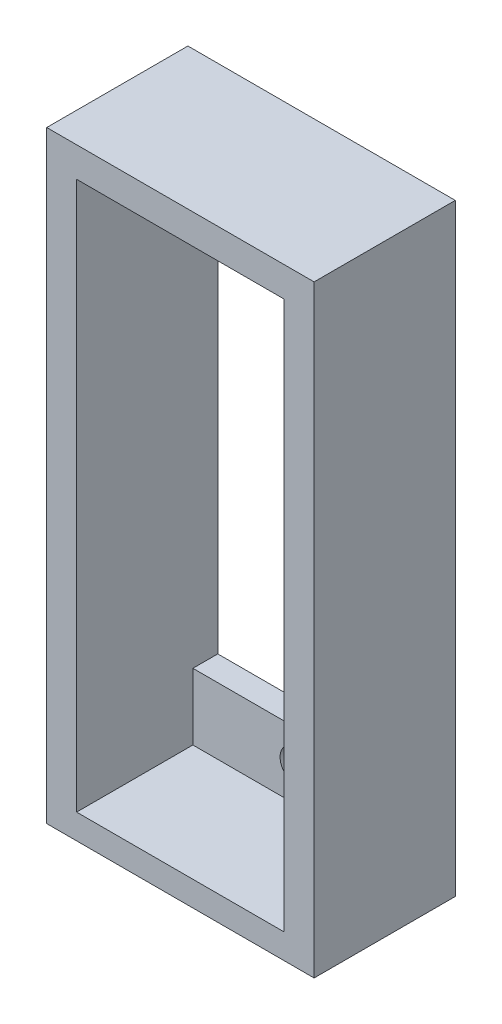
SolidWorks part; units mm, degrees
ref_plane "Alzado" through (0, 0, 0) normal (0, 0, 1) x (1, 0, 0)
ref_plane "Planta" through (0, 0, 0) normal (0, 1, 0) x (1, 0, 0)
ref_plane "Vista lateral" through (0, 0, 0) normal (1, 0, 0) x (0, 0, -1)
sketch "Croquis1" plane through (0, 0, 0) normal (0, 0, 1) x (1, 0, 0)
  circle A0 centre (-51.2357, 9.7866) radius 31.5
  dimension "D1" = 63
extrude "Saliente-Extruir1" add sketch "Croquis1" along normal blind 2.4
sketch "Croquis2" plane through (0, 0, 2.4) normal (0, 0, 1) x (1, 0, 0)
  line L0 (-51.2357, 9.7866) -> (-51.2357, -21.7134) construction
  line L1 (-51.2357, 9.7866) -> (-51.2357, 14.4866) construction
  line L2 (-51.2357, 14.4866) -> (-51.2357, 19.4866) construction
  line L3 (-51.2357, 19.4866) -> (-51.2357, 21.2866) construction
  line L4 (-51.2357, 21.2866) -> (-57.4857, 21.2866) construction
  line L6 (-57.4857, 21.2866) -> (-44.9857, 21.2866)
  line L7 (-57.4857, 21.2866) -> (-57.4857, -11.7134)
  line L8 (-57.4857, -11.7134) -> (-44.9857, -11.7134)
  line L9 (-44.9857, 21.2866) -> (-44.9857, -11.7134)
  line L14 (-59.2857, 23.0866) -> (-43.1857, 23.0866)
  line L15 (-59.2857, 23.0866) -> (-59.2857, -13.2134)
  line L16 (-59.2857, -13.2134) -> (-43.1857, -13.2134)
  line L17 (-43.1857, 23.0866) -> (-43.1857, -13.2134)
  circle A0 centre (-51.2357, 9.7866) radius 31.5 construction
  dimension "D2" = 5
  dimension "D3" = 1.8
  dimension "D4" = 6.25
  dimension "D5" = 12.5
  dimension "D6" = 33
  dimension "D7" = 1.8
  dimension "D8" = 1.8
  dimension "D9" = 1.8
  dimension "D10" = 1.5
  dimension "D11" = 8.5
extrude "Saliente-Extruir2" add sketch "Croquis2" along normal blind 22.5
sketch "Croquis5" plane through (0, 0, 2.4) normal (0, 0, 1) x (1, 0, 0)
  line L1 (-59.2857, 23.0866) -> (-43.1857, 23.0866)
  line L2 (-59.2857, 23.0866) -> (-59.2857, -13.2134)
  line L3 (-59.2857, -13.2134) -> (-43.1857, -13.2134)
  line L4 (-43.1857, 23.0866) -> (-43.1857, -13.2134)
extrude "Cortar-Extruir2" cut sketch "Croquis5" against normal blind 9
sketch "Croquis6" plane through (0, 0, 0) normal (0, 0, -1) x (-1, 0, 0)
  line L6 (51.2357, 9.7866) -> (73.5095, 32.0605) construction
  line L7 (73.5095, 32.0605) -> (73.5095, -12.4873) construction
  line L8 (73.5095, -12.4873) -> (28.9618, 32.0605) construction
  line L9 (28.9618, 32.0605) -> (28.9618, -12.4873) construction
  line L10 (28.9618, -12.4873) -> (51.2357, 9.7866) construction
  line L11 (51.2357, 23.0866) -> (53.2357, 23.0866)
  line L12 (43.1857, 23.0866) -> (59.2857, 23.0866) construction
  line L13 (53.2357, 23.0866) -> (53.2357, 43.0866)
  line L14 (53.2357, 43.0866) -> (49.2357, 43.0866)
  line L15 (49.2357, 43.0866) -> (49.2357, 23.0866)
  line L16 (49.2357, 23.0866) -> (51.2357, 23.0866)
  circle A0 centre (51.2357, 9.7866) radius 31.5 construction
  circle A1 centre (34.6187, 26.4036) radius 1.5
  circle A2 centre (67.8527, 26.4036) radius 1.5
  circle A3 centre (67.8527, -6.8304) radius 1.5
  circle A4 centre (34.6187, -6.8304) radius 1.5
  dimension "D3" = 8
  dimension "D1" = 20
  dimension "D2" = 4
extrude "Cortar-Extruir3" cut sketch "Croquis6" against normal blind 2.4
sketch "Croquis7" plane through (0, 21.2866, 0) normal (0, -1, 0) x (1, 0, 0)
  line L0 (-57.4857, 24.9) -> (-57.4857, 2.4) construction
  line L1 (-57.4857, 17.9) -> (-44.9857, 17.9)
  line L2 (-57.4857, 17.9) -> (-57.4857, 8.9)
  line L3 (-57.4857, 8.9) -> (-44.9857, 8.9)
  line L4 (-44.9857, 17.9) -> (-44.9857, 8.9)
  line L5 (-44.9857, 24.9) -> (-44.9857, 2.4) construction
  line L6 (-44.9857, 24.9) -> (-57.4857, 24.9) construction
  dimension "D1" = 9
  dimension "D2" = 7
extrude "Saliente-Extruir3" add sketch "Croquis7" along normal up to vertex (33 mm away)
sketch "Croquis8" plane through (0, 0, 17.9) normal (0, 0, 1) x (1, 0, 0)
  line L0 (-44.9857, -11.7134) -> (-44.9857, 21.2866) construction
  line L1 (-44.9857, -7.7134) -> (-57.4857, -7.7134)
  line L2 (-44.9857, -7.7134) -> (-44.9857, 15.2866)
  line L4 (-57.4857, -7.7134) -> (-57.4857, 15.2866)
  line L5 (-57.4857, -11.7134) -> (-57.4857, 21.2866) construction
  line L6 (-44.9857, -11.7134) -> (-57.4857, -11.7134) construction
  line L9 (-44.9857, 15.2866) -> (-49.2357, 15.2866)
  line L10 (-49.2357, 15.2866) -> (-49.2357, 17.2866)
  line L11 (-49.2357, 17.2866) -> (-53.2357, 17.2866)
  line L12 (-53.2357, 17.2866) -> (-53.2357, 15.2866)
  line L13 (-53.2357, 15.2866) -> (-57.4857, 15.2866)
  line L14 (-44.9857, 21.2866) -> (-57.4857, 21.2866) construction
  circle A0 centre (-51.2357, -9.7134) radius 1
  circle A1 centre (-51.2357, 18.3366) radius 1
  dimension "D3" = 2
  dimension "D6" = 2.95
  dimension "D1" = 4
  dimension "D2" = 6
  dimension "D4" = 4
  dimension "D5" = 2
  dimension "D7" = 2
extrude "Cortar-Extruir5" cut sketch "Croquis8" against normal blind 9
sketch "Croquis9" plane through (-44.9857, 0, 0) normal (-1, 0, 0) x (0, 0, 1)
  line L0 (8.9, -7.7134) -> (3.9, -11.7134)
  line L1 (8.9, -11.7134) -> (2.4, -11.7134) construction
  line L2 (3.9, -11.7134) -> (8.9, -11.7134)
  line L3 (8.9, -11.7134) -> (8.9, -7.7134)
  line L4 (8.9, 15.2866) -> (4.1, 21.2866)
  line L5 (8.9, 21.2866) -> (2.4, 21.2866) construction
  line L6 (4.1, 21.2866) -> (8.9, 21.2866)
  line L7 (8.9, 21.2866) -> (8.9, 15.2866)
extrude "Saliente-Extruir4" add sketch "Croquis9" along normal up to vertex (12.5 mm away)
sketch "Croquis10" plane through (0, 0, 8.9) normal (0, 0, 1) x (1, 0, 0)
  line L1 (-53.2357, 15.2866) -> (-49.2357, 15.2866)
  line L2 (-53.2357, 15.2866) -> (-53.2357, 17.2866)
  line L3 (-53.2357, 17.2866) -> (-49.2357, 17.2866)
  line L4 (-49.2357, 15.2866) -> (-49.2357, 17.2866)
extrude "Cortar-Extruir6" cut sketch "Croquis10" against normal blind 9
sketch "Croquis11" plane through (0, 0, 2.4) normal (0, 0, -1) x (-1, 0, 0)
  line L0 (49.2357, 23.0866) -> (43.1857, 23.0866)
  line L1 (43.1857, 23.0866) -> (43.1857, -13.2134)
  line L2 (43.1857, -13.2134) -> (59.2857, -13.2134)
  line L3 (59.2857, -13.2134) -> (59.2857, 23.0866)
  line L4 (59.2857, 23.0866) -> (53.2357, 23.0866)
  line L5 (53.2357, 23.0866) -> (53.2357, 21.2866)
  line L6 (44.9857, 21.2866) -> (57.4857, 21.2866) construction
  line L7 (53.2357, 21.2866) -> (57.4857, 21.2866)
  line L8 (57.4857, 21.2866) -> (57.4857, 10.5866)
  line L9 (57.4857, 21.2866) -> (57.4857, -11.7134) construction
  line L10 (57.4857, 10.5866) -> (44.9857, 10.5866)
  line L11 (44.9857, -11.7134) -> (44.9857, 21.2866) construction
  line L12 (44.9857, 10.5866) -> (44.9857, 21.2866)
  line L13 (44.9857, 21.2866) -> (49.2357, 21.2866)
  line L14 (49.2357, 21.2866) -> (49.2357, 23.0866)
extrude "Saliente-Extruir5" add sketch "Croquis11" along normal up to vertex (2.4 mm away)
sketch "Croquis12" plane through (-43.1857, 0, 0) normal (1, 0, 0) x (0, 0, -1)
  line L0 (-2.4, 23.0866) -> (-7.4, 23.0866)
  line L1 (-24.9, 23.0866) -> (-2.4, 23.0866) construction
  line L2 (-7.4, 23.0866) -> (-2.4, 29.3866)
  line L3 (-2.4, 29.3866) -> (-2.4, 23.0866)
extrude "Saliente-Extruir6" add sketch "Croquis12" against normal up to vertex (16.1 mm away) up to point (-59.2857, 23.0866, 24.9)
sketch "Croquis13" plane through (0, 0, 2.4) normal (0, 0, 1) x (1, 0, 0)
  line L1 (-31.3855, -6.8304) -> (-33.0021, -4.0304)
  line L2 (-33.0021, -4.0304) -> (-36.2352, -4.0304)
  line L3 (-36.2352, -4.0304) -> (-37.8518, -6.8304)
  line L4 (-37.8518, -6.8304) -> (-36.2352, -9.6304)
  line L5 (-36.2352, -9.6304) -> (-33.0021, -9.6304)
  line L6 (-33.0021, -9.6304) -> (-31.3855, -6.8304)
  line L7 (-64.6195, -6.8304) -> (-66.2361, -4.0304)
  line L8 (-66.2361, -4.0304) -> (-69.4693, -4.0304)
  line L9 (-69.4693, -4.0304) -> (-71.0858, -6.8304)
  line L10 (-71.0858, -6.8304) -> (-69.4693, -9.6304)
  line L11 (-69.4693, -9.6304) -> (-66.2361, -9.6304)
  line L12 (-66.2361, -9.6304) -> (-64.6195, -6.8304)
  line L13 (-37.8518, 26.4036) -> (-36.2352, 23.6036)
  line L14 (-36.2352, 23.6036) -> (-33.0021, 23.6036)
  line L15 (-33.0021, 23.6036) -> (-31.3855, 26.4036)
  line L16 (-31.3855, 26.4036) -> (-33.0021, 29.2036)
  line L17 (-33.0021, 29.2036) -> (-36.2352, 29.2036)
  line L18 (-36.2352, 29.2036) -> (-37.8518, 26.4036)
  line L19 (-71.0858, 26.4036) -> (-69.4693, 23.6036)
  line L20 (-69.4693, 23.6036) -> (-66.2361, 23.6036)
  line L21 (-66.2361, 23.6036) -> (-64.6195, 26.4036)
  line L22 (-64.6195, 26.4036) -> (-66.2361, 29.2036)
  line L23 (-66.2361, 29.2036) -> (-69.4693, 29.2036)
  line L24 (-69.4693, 29.2036) -> (-71.0858, 26.4036)
  circle A0 centre (-34.6187, -6.8304) radius 2.8 construction
  circle A1 centre (-67.8527, -6.8304) radius 2.8 construction
  circle A2 centre (-34.6187, 26.4036) radius 2.8 construction
  circle A3 centre (-67.8527, 26.4036) radius 2.8 construction
  dimension "D1" = 5.6
  dimension "D2" = 5.6
extrude "Cortar-Extruir7" cut sketch "Croquis13" against normal blind 1.8
sketch "Croquis14" plane through (0, 0, 0) normal (0, 0, -1) x (-1, 0, 0)
  line L0 (53.2357, 41.223) -> (53.2357, 21.2866)
  line L1 (53.2357, 21.2866) -> (57.4857, 21.2866)
  line L2 (57.4857, 21.2866) -> (57.4857, 10.5866)
  line L3 (57.4857, 10.5866) -> (44.9857, 10.5866)
  line L4 (44.9857, 10.5866) -> (44.9857, 21.2866)
  line L5 (44.9857, 21.2866) -> (49.2357, 21.2866)
  line L6 (49.2357, 21.2866) -> (49.2357, 41.223)
  arc A0 (53.2357, 41.223) -> (49.2357, 41.223) centre (51.2357, 9.7866) cw
  circle A1 centre (67.8527, -6.8304) radius 1.5
  circle A2 centre (34.6187, -6.8304) radius 1.5
  circle A3 centre (34.6187, 26.4036) radius 1.5
  circle A4 centre (67.8527, 26.4036) radius 1.5
extrude "Saliente-Extruir7" add sketch "Croquis14" along normal blind 0.6
sketch "Croquis15" plane through (0, -7.7134, 0) normal (0, 1, 0) x (1, 0, 0)
  line L0 (-44.9857, -16.4) -> (-57.4857, -16.4) construction
  line L1 (-44.9857, -8.9) -> (-44.9857, -17.9) construction
  line L2 (-57.4857, -8.9) -> (-57.4857, -17.9) construction
  line L3 (-57.4857, -17.9) -> (-44.9857, -17.9) construction
  dimension "D1" = 1.5
ref_plane "Plano1" through (0, 0, 16.4) normal (0, 0, 1) x (1, 0, 0)
sketch "Croquis17" plane through (0, 0, 16.4) normal (0, 0, 1) x (1, 0, 0)
  circle A0 centre (-51.7498, 10.1318) radius 41.4532
extrude "Cortar-Extruir8" cut sketch "Croquis17" against normal up to vertex
